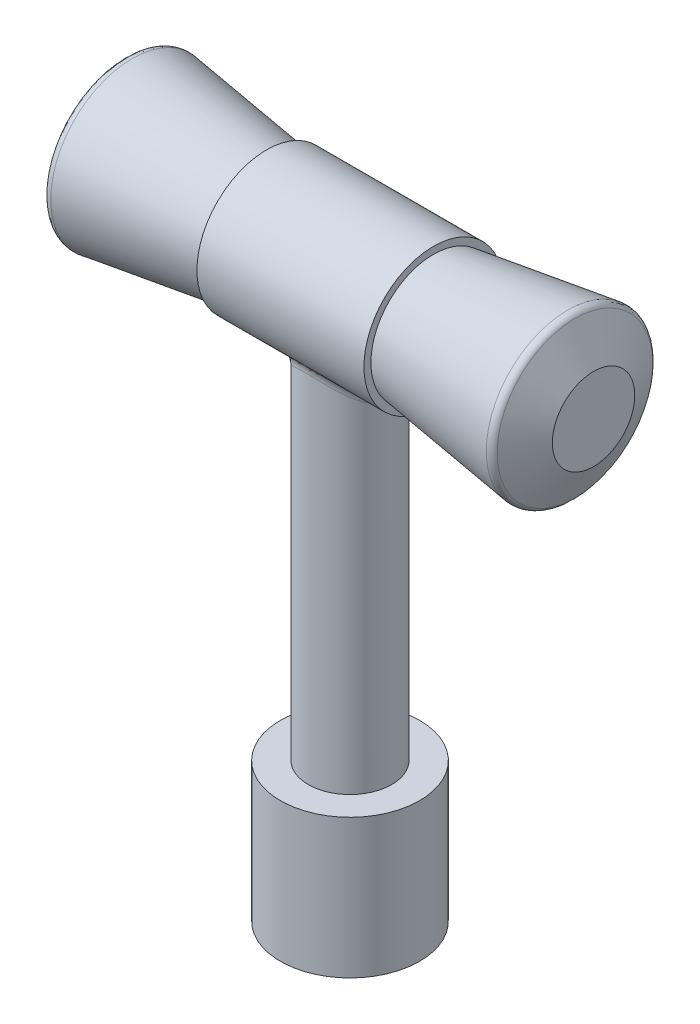
SolidWorks part; units mm, degrees
ref_plane "Front Plane" through (0, 0, 0) normal (0, 0, 1) x (1, 0, 0)
ref_plane "Top Plane" through (0, 0, 0) normal (0, 1, 0) x (1, 0, 0)
ref_plane "Right Plane" through (0, 0, 0) normal (1, 0, 0) x (0, 0, -1)
sketch "Sketch3" plane through (0, 0, 0) normal (1, 0, 0) x (0, 0, -1)
  line L0 (0, 41.7347) -> (0, -9.4448) construction
  line L1 (-8.6515, 40) -> (10.2151, 40) construction
  circle A0 centre (0, 40) radius 5
  dimension "D1" = 10
extrude "Boss-Extrude1" add sketch "Sketch3" along normal mid plane 12 separate body
sketch "Sketch4" plane through (6, 0, 0) normal (1, 0, 0) x (0, 0, -1)
  circle A0 centre (0, 40) radius 4.5
  circle A1 centre (0, 40) radius 5 construction
  dimension "D1" = 9
extrude "Boss-Extrude2" add sketch "Sketch4" along normal blind 10 draft 8 draft outward yes
mirror "Mirror1" about plane through (0, 0, 0) normal (1, 0, 0) of "Boss-Extrude2"
ref_plane "Plane1" through (0, 35, 0) normal (0, -1, 0) x (-1, 0, 0)
sketch "Sketch5" plane through (0, 35, 0) normal (0, -1, 0) x (-1, 0, 0)
  circle A0 centre (0, 0) radius 3
  dimension "D1" = 6
extrude "Boss-Extrude3" add sketch "Sketch5" along normal blind 25 and the other way up to next
sketch "Sketch6" plane through (0, 10, 0) normal (0, -1, 0) x (1, 0, 0)
  circle A0 centre (0, 0) radius 5
  dimension "D1" = 10
extrude "Boss-Extrude4" add sketch "Sketch6" along normal blind 10
cosmetic thread "Cosmetic Thread1" parameters "D2"=8.5
hole_wizard "Ø5.0mm Dowel Hole1" positions "Sketch7" profile "Sketch8" hole size "Ø5.0" standard "ANSI Metric"
sketch "Sketch7" plane through (0, 0, 0) normal (0, -1, 0) x (-1, 0, 0)
  point P0 (0, 0)
sketch "Sketch8" plane through (0, 0, 0) normal (1, 0, 0) x (0, 0, -1)
  line L0 (0, 0) -> (0, 11.5022)
  line L1 (0, 11.5022) -> (2.5, 10)
  line L2 (2.5, 10) -> (2.5, 0)
  line L5 (2.5, 0) -> (0, 0)
  line L10 (0, 11.5022) -> (-2.5, 10) construction
  line L11 (0, -6.35) -> (0, 107.95) construction
  dimension "Hole Dia." = 5
  dimension "Hole Depth" = 10
  dimension "Drill Angle" = 118
sketch "Sketch9" plane through (16, 0, 0) normal (1, 0, 0) x (0, 0, -1)
  circle A0 centre (0, 40) radius 5.9054
extrude "Boss-Extrude5" add sketch "Sketch9" along normal blind 1.5 draft 63
mirror "Mirror2" about plane through (0, 0, 0) normal (1, 0, 0) of "Boss-Extrude5"
fillet "Fillet1" radius 1 1 edges at (-0.0065, 36, -3)
fillet "Fillet2" radius 0.5 2 edges at (16, 40, -5.9054) (-16, 40, -5.9054)
